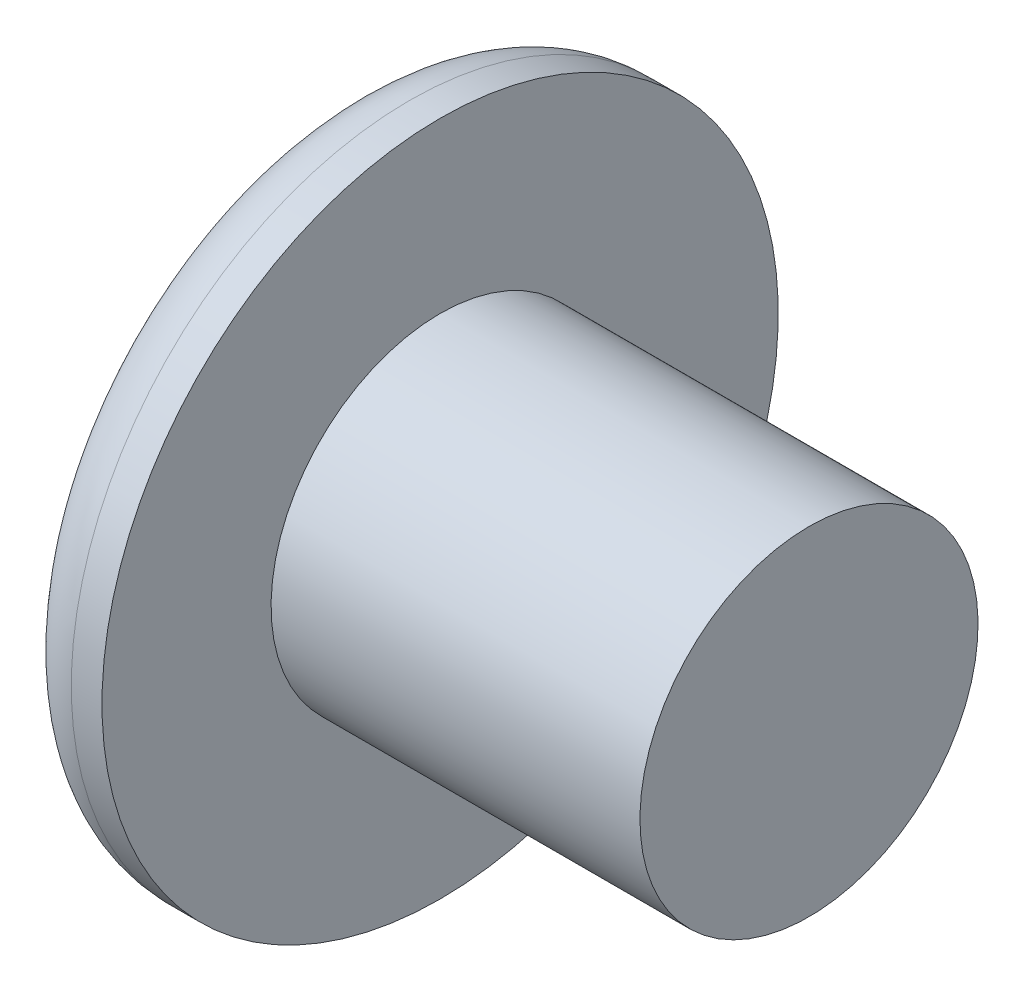
SolidWorks part; units mm, degrees
ref_plane "Front Plane" through (0, 0, 0) normal (0, 0, 1) x (1, 0, 0)
ref_plane "Top Plane" through (0, 0, 0) normal (0, 1, 0) x (1, 0, 0)
ref_plane "Right Plane" through (0, 0, 0) normal (1, 0, 0) x (0, 0, -1)
sketch "Sketch1" plane through (0, 0, 0) normal (0, 0, 1) x (1, 0, 0)
  line L0 (0, 0) -> (0, 11)
  line L1 (0, 11) -> (3, 11)
  line L2 (3, 11) -> (3, 0)
  line L3 (3, 0) -> (0, 0)
  line L4 (3, 5.5) -> (15, 5.5)
  line L5 (15, 5.5) -> (15, 0)
  line L6 (15, 0) -> (3, 0)
  dimension "D1" = 3
  dimension "D2" = 12
  dimension "D3" = 11
  dimension "D4" = 5.5
revolve "Revolve1" add sketch "Sketch1" angle 360 about L6
fillet "Fillet1" radius 2 1 edges at (0, 11, 0)
